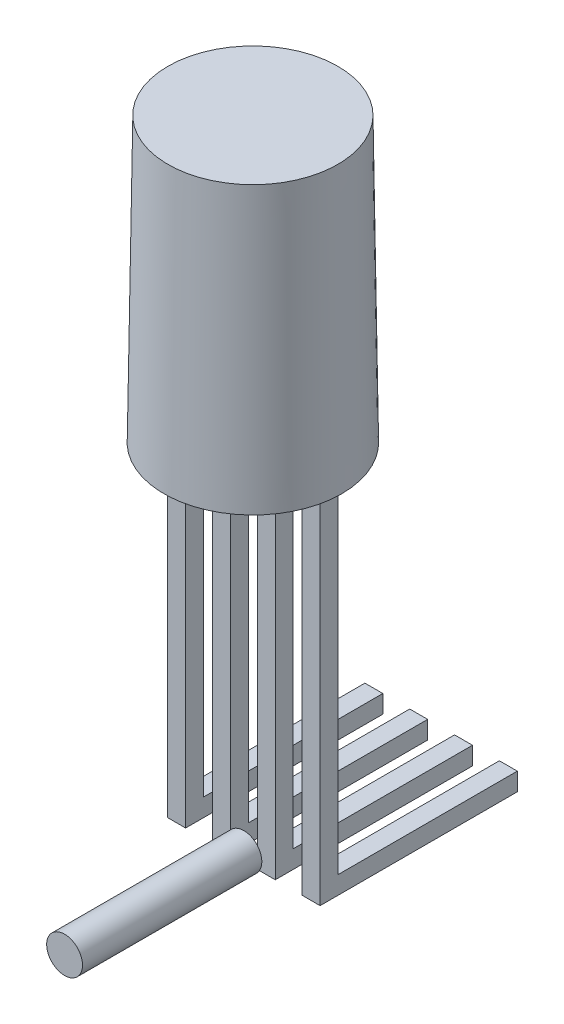
SolidWorks part; units mm, degrees
ref_plane "Front Plane" through (0, 0, 0) normal (0, 0, 1) x (1, 0, 0)
ref_plane "Top Plane" through (0, 0, 0) normal (0, 1, 0) x (1, 0, 0)
ref_plane "Right Plane" through (0, 0, 0) normal (1, 0, 0) x (0, 0, -1)
sketch "Sketch2" plane through (0, 0, 0) normal (0, 0, 1) x (1, 0, 0)
  line L0 (0, 0) -> (2.48, 0)
  line L1 (2.48, 0) -> (2.37, 7.9)
  line L2 (2.37, 7.9) -> (0, 7.9)
  line L3 (0, 7.9) -> (0, 0)
  dimension "D1" = 2.48
  dimension "D2" = 2.37
  dimension "D3" = 7.9
revolve "Revolve1" add sketch "Sketch2" angle 360 about L3
sketch "Sketch3" plane through (0, 0, 0) normal (0, -1, 0) x (1, 0, 0)
  line L0 (-0.875, -0.25) -> (-0.875, 0.25)
  line L1 (-2.125, -0.25) -> (-1.625, -0.25)
  line L2 (-2.125, -0.25) -> (-2.125, 0.25)
  line L3 (-2.125, 0.25) -> (-1.625, 0.25)
  line L4 (-1.625, -0.25) -> (-1.625, 0.25)
  line L5 (-2.125, -0.25) -> (-1.625, 0.25) construction
  line L6 (-2.125, 0.25) -> (-1.625, -0.25) construction
  line L7 (-0.875, -0.25) -> (-0.375, -0.25)
  line L8 (-0.375, -0.25) -> (-0.375, 0.25)
  line L9 (-0.875, 0.25) -> (-0.375, 0.25)
  line L10 (0.375, -0.25) -> (0.375, 0.25)
  line L11 (0.375, -0.25) -> (0.875, -0.25)
  line L12 (0.875, -0.25) -> (0.875, 0.25)
  line L13 (0.375, 0.25) -> (0.875, 0.25)
  line L14 (1.625, -0.25) -> (1.625, 0.25)
  line L15 (1.625, -0.25) -> (2.125, -0.25)
  line L16 (2.125, -0.25) -> (2.125, 0.25)
  line L17 (1.625, 0.25) -> (2.125, 0.25)
  line L18 (-0.375, 0.25) -> (0.375, 0.25) construction
  point P0 (-1.875, 0)
  point P7 (-0.625, 0.25)
  point P19 (0, 0.25)
  dimension "D2" = 1.25
  dimension "D3" = 0.5
  dimension "D4" = 0.5
  dimension "D1" = 4
extrude "Boss-Extrude1" add sketch "Sketch3" along normal blind 10
sketch "Sketch4" plane through (0, 0, -0.25) normal (0, 0, 1) x (1, 0, 0)
  line L0 (-1.625, -10) -> (-1.625, 0) construction
  line L1 (-2.125, -10) -> (-1.625, -10)
  line L2 (-2.125, -10) -> (-2.125, -9.5)
  line L3 (-2.125, -9.5) -> (-1.625, -9.5)
  line L4 (-1.625, -10) -> (-1.625, -9.5)
  line L5 (-0.875, -10) -> (-0.875, -9.5)
  line L6 (-0.875, -10) -> (-0.375, -10)
  line L7 (-0.375, -10) -> (-0.375, -9.5)
  line L8 (-0.875, -9.5) -> (-0.375, -9.5)
  line L9 (0.375, -10) -> (0.375, -9.5)
  line L10 (0.375, -10) -> (0.875, -10)
  line L11 (0.875, -10) -> (0.875, -9.5)
  line L12 (0.375, -9.5) -> (0.875, -9.5)
  line L13 (1.625, -10) -> (1.625, -9.5)
  line L14 (1.625, -10) -> (2.125, -10)
  line L15 (2.125, -10) -> (2.125, -9.5)
  line L16 (1.625, -9.5) -> (2.125, -9.5)
  line L17 (2.125, -10) -> (2.125, 0) construction
  point P8 (0, 0)
  dimension "D1" = 0.5
  dimension "D2" = 4
extrude "Boss-Extrude2" add sketch "Sketch4" against normal blind 5
sketch "Sketch5" plane through (0, 0, 0.25) normal (0, 0, 1) x (1, 0, 0)
  line L0 (-0.875, -10) -> (0.875, -9.5) construction
  circle A0 centre (0, -9.75) radius 0.5
  dimension "D1" = 1
extrude "Boss-Extrude3" add sketch "Sketch5" along normal blind 5
